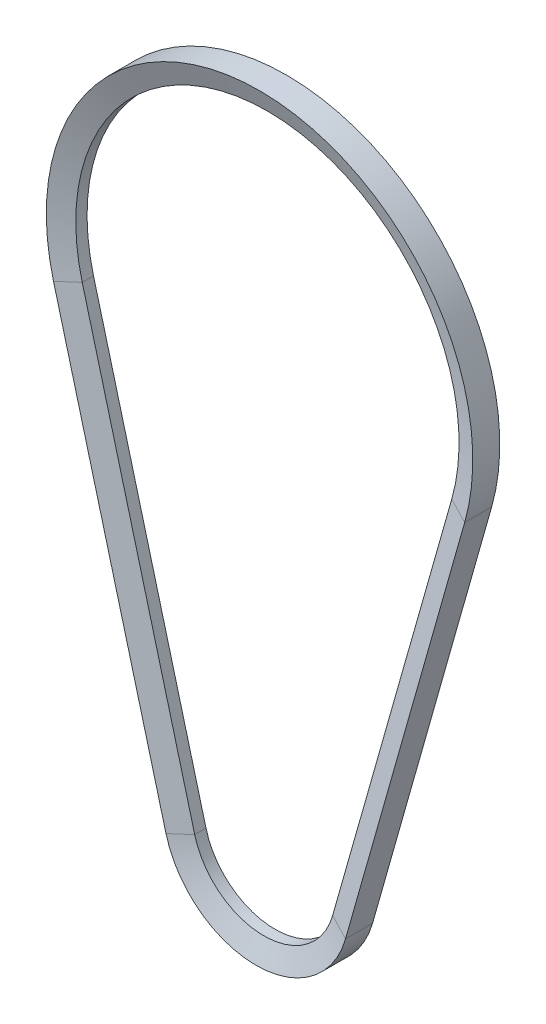
SolidWorks part; units mm, degrees
ref_plane "Front Plane" through (0, 0, 0) normal (0, 0, 1) x (1, 0, 0)
ref_plane "Top Plane" through (0, 0, 0) normal (0, 1, 0) x (1, 0, 0)
ref_plane "Right Plane" through (0, 0, 0) normal (1, 0, 0) x (0, 0, -1)
sketch "Sketch2" plane through (0, 0, 0) normal (0, 0, 1) x (1, 0, 0)
  line L0 (0, 0) -> (1, 0) construction
  line L1 (0, 0) -> (0, 1) construction
  line L2 (67.3449, -19.0963) -> (23.2031, -174.7666)
  line L3 (-25.9696, -174.377) -> (-67.639, -18.0267)
  arc A0 (-67.639, -18.0267) -> (67.3449, -19.0963) centre (0, 0) cw
  arc A1 (23.2031, -174.7666) -> (-25.9696, -174.377) centre (-1.3297, -167.8101) cw
ref_plane "Plane1" through (-67.639, -18.0267, 0) normal (-0.2575, 0.9663, 0) x (0.9663, 0.2575, 0)
sketch "Sketch3" plane through (-67.639, -18.0267, 0) normal (-0.2575, 0.9663, 0) x (0.9663, 0.2575, 0)
  line L0 (-1, 2.0882) -> (-1, -2.0882)
  line L1 (-1, -2.0882) -> (-9, -5)
  line L2 (-9, -5) -> (-9, 5)
  line L3 (-9, 5) -> (-1, 2.0882)
  line L4 (-1, 0) -> (-11.362, 0) construction
  line L5 (-2.3179, 0) -> (0, 0) construction
  point P6 (-2.3179, 0)
  dimension "D1" = 1
  dimension "D2" = 8
  dimension "D3" = 10
  dimension "D4" = 40
sweep "Sweep1" add profiles "Sketch3" path "Sketch2"
